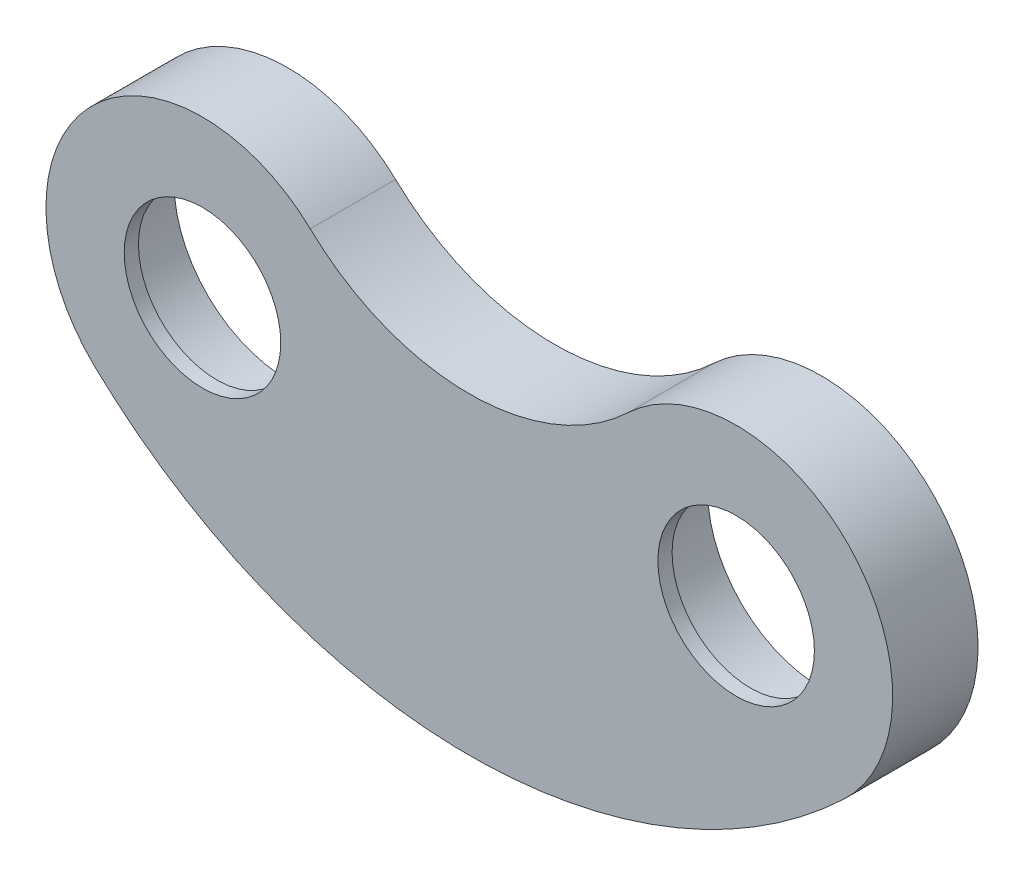
SolidWorks part; units mm, degrees
ref_plane "Alzado" through (0, 0, 0) normal (0, 0, 1) x (1, 0, 0)
ref_plane "Planta" through (0, 0, 0) normal (0, 1, 0) x (1, 0, 0)
ref_plane "Vista lateral" through (0, 0, 0) normal (1, 0, 0) x (0, 0, -1)
sketch "Croquis1" plane through (0, 0, 0) normal (0, 0, 1) x (1, 0, 0)
  line L0 (33.0911, 0.5584) -> (33.0911, -8.5648) construction
  line L1 (-4.4089, -44.8135) -> (-4.4089, 44.3305) construction
  line L2 (-41.9089, 0.5584) -> (33.0911, 0.5584) construction
  line L3 (-41.9089, 0.5584) -> (-41.9089, -13.6007) construction
  arc A0 (-26.7712, 16.5225) -> (-57.0465, -15.4057) centre (-41.9089, 0.5584) ccw
  arc A1 (48.2288, -15.4057) -> (17.9535, 16.5225) centre (33.0911, 0.5584) ccw
  circle A2 centre (-41.9089, 0.5584) radius 11
  circle A3 centre (33.0911, 0.5584) radius 11
  arc A4 (-57.0465, -15.4057) -> (48.2288, -15.4057) centre (-4.4089, 40.1058) ccw
  arc A5 (-26.7712, 16.5225) -> (17.9535, 16.5225) centre (-4.4089, 40.1058) ccw
  point P2 (0, 0)
  dimension "D2" = 22
  dimension "D4" = 22
  dimension "D5" = 65
  dimension "D3" = 37.5
  dimension "D6" = 32.5
  dimension "D7" = 39.5474
  dimension "D1" = 75
extrude "Saliente-Extruir1" add sketch "Croquis1" along normal blind 12
sketch "Croquis3" plane through (0, 0, 0) normal (0, 0, -1) x (-1, 0, 0)
  circle A0 centre (41.9089, 0.5584) radius 16
  circle A1 centre (-33.0911, 0.5584) radius 16
  dimension "D1" = 32
  dimension "D2" = 32
extrude "Cortar-Extruir2" cut sketch "Croquis3" against normal blind 10
